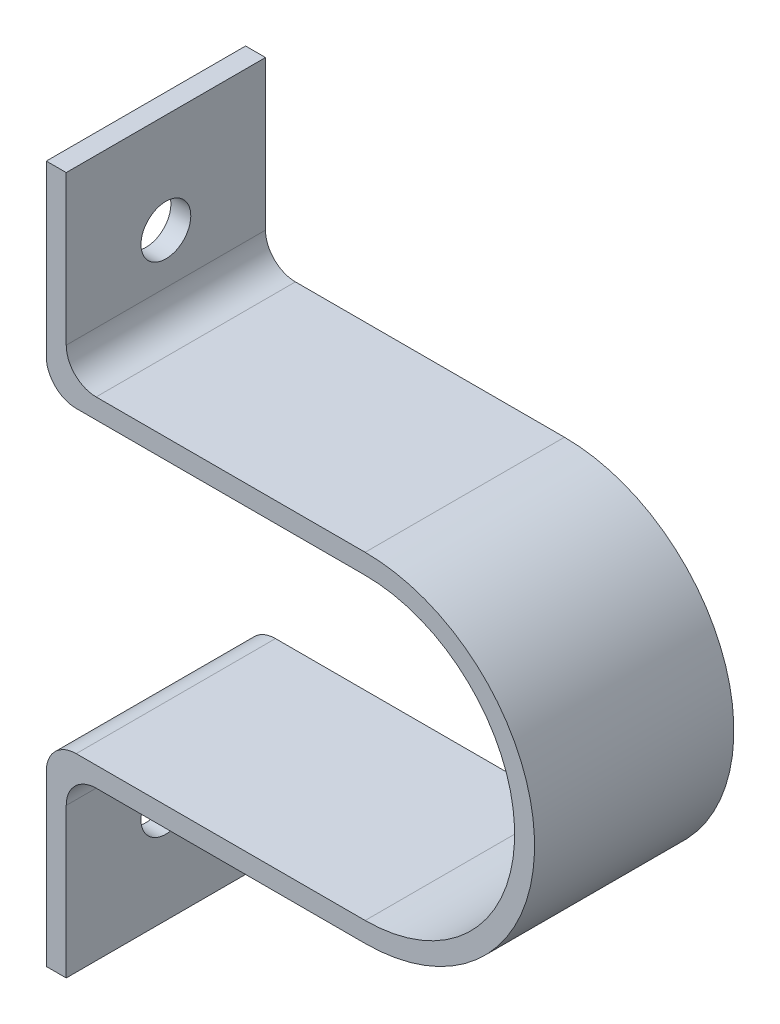
SolidWorks part; units mm, degrees
ref_plane "Front Plane" through (0, 0, 0) normal (0, 0, 1) x (1, 0, 0)
ref_plane "Top Plane" through (0, 0, 0) normal (0, 1, 0) x (1, 0, 0)
ref_plane "Right Plane" through (0, 0, 0) normal (1, 0, 0) x (0, 0, -1)
sketch "Sketch1" plane through (0, 0, 0) normal (0, 0, 1) x (1, 0, 0)
  line L0 (40, -5) -> (8, -5)
  line L1 (8, 26.5477) -> (8, -55) construction
  line L2 (8, -5) -> (8, 15)
  line L3 (40, -35) -> (8, -35)
  line L4 (8, -35) -> (8, -55)
  line L5 (10, -37) -> (10, -55)
  line L6 (40, -37) -> (10, -37)
  line L7 (40, -3) -> (10, -3)
  line L8 (10, -3) -> (10, 15)
  line L9 (8, 15) -> (10, 15)
  line L10 (8, -55) -> (10, -55)
  arc A0 (40, -35) -> (40, -5) centre (40, -20) ccw
  arc A1 (40, -37) -> (40, -3) centre (40, -20) ccw
  dimension "D2" = 20
  dimension "D3" = 20
  dimension "D1" = 2
extrude "Boss-Extrude1" add sketch "Sketch1" against normal blind 20 from offset 10
sketch "Sketch2" plane through (10, 0, 0) normal (1, 0, 0) x (0, 0, -1)
  line L0 (30, -3) -> (30, 15) construction
  line L1 (30, 15) -> (10, 15) construction
  line L2 (30, -55) -> (10, -55) construction
  circle A0 centre (20, 5) radius 2.5
  circle A1 centre (20, -45) radius 2.5
  dimension "D1" = 5
  dimension "D2" = 5
  dimension "D3" = 10
  dimension "D4" = 10
  dimension "D5" = 10
extrude "Cut-Extrude1" cut sketch "Sketch2" against normal through all
fillet "Fillet1" radius 3 4 edges at (10, -37, -20) (8, -35, -20) (8, -5, -20) (10, -3, -20)
